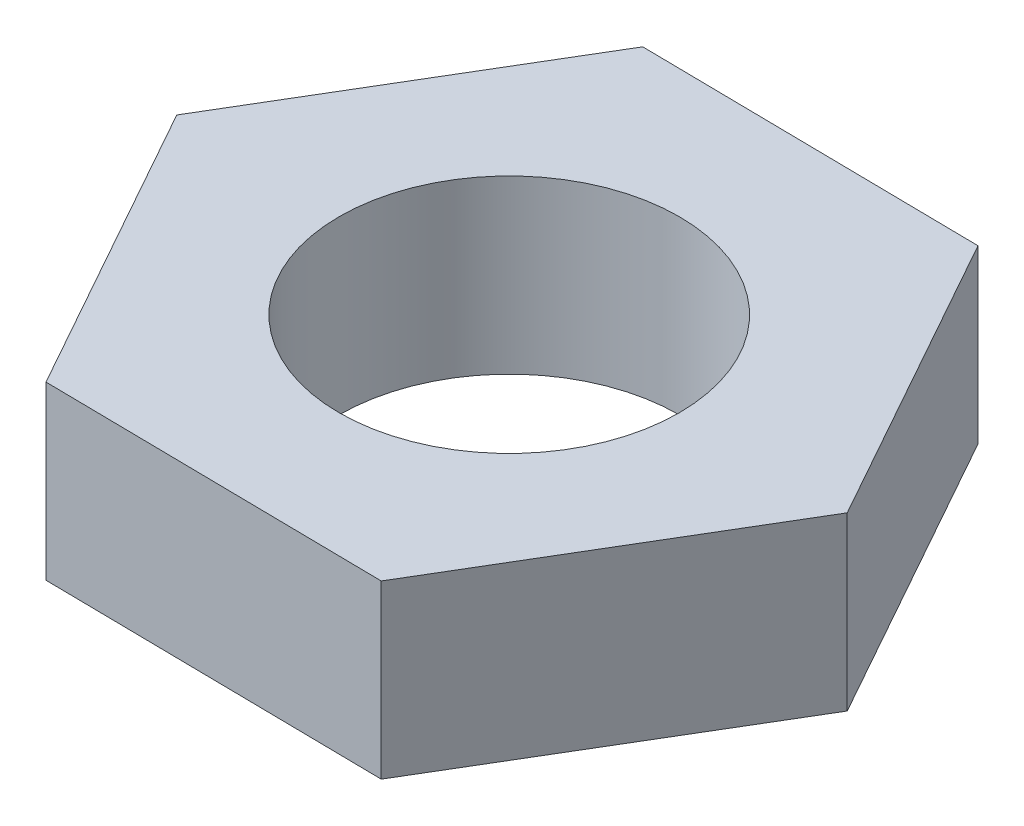
SolidWorks part; units mm, degrees
ref_plane "Front Plane" through (0, 0, 0) normal (0, 0, 1) x (1, 0, 0)
ref_plane "Top Plane" through (0, 0, 0) normal (0, 1, 0) x (1, 0, 0)
ref_plane "Right Plane" through (0, 0, 0) normal (1, 0, 0) x (0, 0, -1)
sketch "Sketch1" plane through (0, 0, 0) normal (0, 1, 0) x (1, 0, 0)
  line L1 (7.5718, 5.4109) -> (2.4922, 5.4805)
  line L2 (2.4922, 5.4805) -> (-0.1077, 1.1162)
  line L3 (-0.1077, 1.1162) -> (2.3718, -3.3175)
  line L4 (2.3718, -3.3175) -> (7.4514, -3.3871)
  line L5 (7.4514, -3.3871) -> (10.0513, 0.9772)
  line L6 (10.0513, 0.9772) -> (7.5718, 5.4109)
  circle A0 centre (4.9718, 1.0467) radius 4.3994 construction
  dimension "D2" = 5.08
extrude "Boss-Extrude1" add sketch "Sketch1" along normal blind 2.5654 contours L3 L4 L5 L6 L1 L2
sketch "Sketch3" plane through (0, 2.5654, 0) normal (0, 1, 0) x (1, 0, 0)
  circle A0 centre (4.9616, 1.0154) radius 2.54
extrude "Cut-Extrude1" cut sketch "Sketch3" against normal through all
